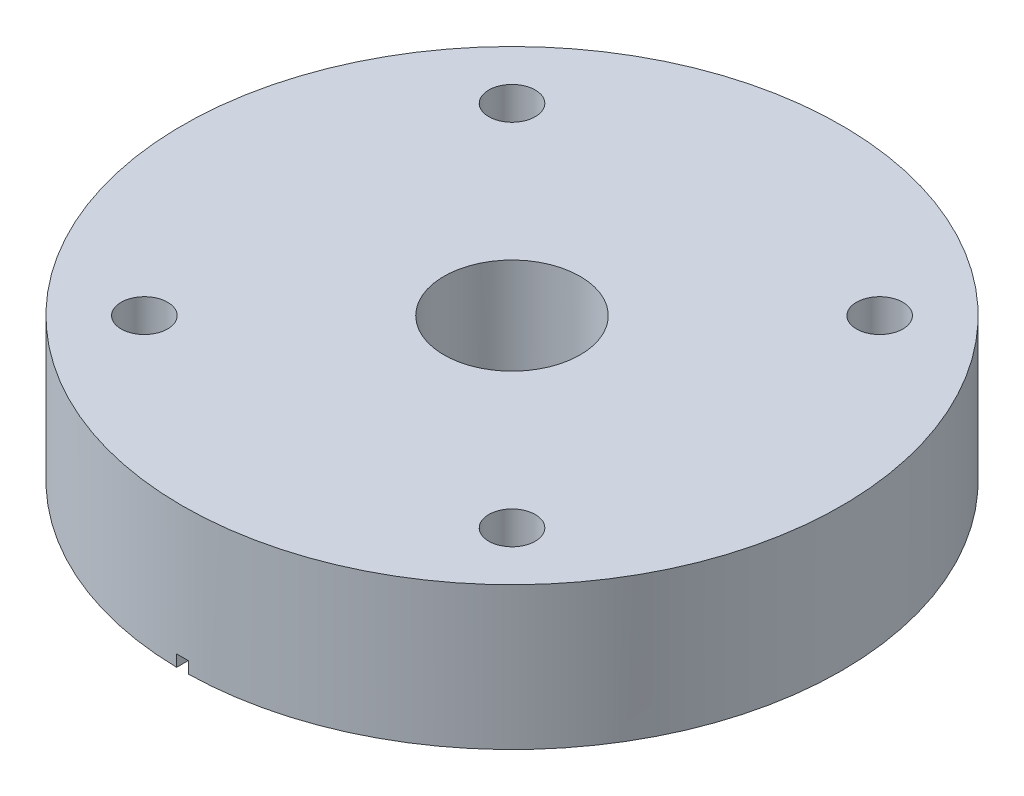
SolidWorks part; units mm, degrees
material "1060 Alloy"
ref_plane "Front" through (0, 0, 0) normal (0, 0, 1) x (1, 0, 0)
ref_plane "Top" through (0, 0, 0) normal (0, 1, 0) x (1, 0, 0)
ref_plane "Right" through (0, 0, 0) normal (1, 0, 0) x (0, 0, -1)
sketch "Sketch1" plane through (0, 0, 0) normal (0, 1, 0) x (1, 0, 0)
  line L0 (0, 0) -> (0, 44.45) construction
  circle A0 centre (-31.4309, 31.4309) radius 3.9688
  circle A1 centre (31.4309, 31.4309) radius 3.9687
  circle A2 centre (31.4309, -31.4309) radius 3.9687
  circle A3 centre (-31.4309, -31.4309) radius 3.9688
  circle A4 centre (0, 0) radius 10.1459
  arc A5 (-24.1039, 40.8157) -> (-40.8157, 24.1039) centre (-31.4309, 31.4309) ccw construction
  arc A6 (40.8157, 24.1039) -> (24.1039, 40.8157) centre (31.4309, 31.4309) ccw construction
  arc A7 (24.1039, -40.8157) -> (40.8157, -24.1039) centre (31.4309, -31.4309) ccw construction
  arc A8 (-40.8157, -24.1039) -> (-24.1039, -40.8157) centre (-31.4309, -31.4309) ccw construction
  arc A9 (-40.2313, 18.9009) -> (-40.2313, -18.9009) centre (0, 0) ccw construction
  arc A10 (-18.9009, -40.2313) -> (18.9009, -40.2313) centre (0, 0) ccw construction
  arc A11 (40.2313, -18.9009) -> (40.2313, 18.9009) centre (0, 0) ccw construction
  arc A12 (-18.9009, 40.2313) -> (-24.1039, 40.8157) centre (-21.027, 44.7568) cw construction
  arc A13 (18.9009, 40.2313) -> (-18.9009, 40.2313) centre (0, 0) ccw construction
  arc A14 (24.1039, 40.8157) -> (18.9009, 40.2313) centre (21.027, 44.7568) cw construction
  arc A15 (40.8157, 24.1039) -> (40.2313, 18.9009) centre (44.7568, 21.027) ccw construction
  arc A16 (40.2313, -18.9009) -> (40.8157, -24.1039) centre (44.7568, -21.027) ccw construction
  arc A17 (24.1039, -40.8157) -> (18.9009, -40.2313) centre (21.027, -44.7568) ccw construction
  arc A18 (-18.9009, -40.2313) -> (-24.1039, -40.8157) centre (-21.027, -44.7568) ccw construction
  arc A19 (-40.2313, -18.9009) -> (-40.8157, -24.1039) centre (-44.7568, -21.027) cw construction
  arc A20 (-40.2313, 18.9009) -> (-40.8157, 24.1039) centre (-44.7568, 21.027) ccw construction
  circle A21 centre (0, 0) radius 56.3562
  point P0 (0, 0)
  point P17 (0, 0)
  point P27 (0, 0)
  dimension "D5" = 7.9375
  dimension "D6" = 20.2918
  dimension "D1" = 5
  dimension "D2" = 11.9062
  dimension "D3" = 44.45
  dimension "D4" = 4
  dimension "D8" = 4
extrude "body and main holes" add sketch "Sketch1" along normal blind 24.4122
sketch "Sketch3" plane through (0, 24.4122, 0) normal (0, -1, 0) x (1, 0, 0)
  circle A0 centre (0, 0) radius 11.6459
  dimension "D1" = 23.2918
extrude "seal bore" cut sketch "Sketch3" along normal blind 22.4122
sketch "Sketch4" plane through (0, 0, 0) normal (0, -1, 0) x (1, 0, 0)
  line L0 (0, 0) -> (0, 44.45) construction
  line L2 (-1, 56.3563) -> (1, 56.3563)
  line L3 (-1, 56.3563) -> (-1, -56.3562)
  line L4 (-1, -56.3562) -> (1, -56.3562)
  line L5 (1, 56.3563) -> (1, -56.3562)
  line L6 (-1, 56.3563) -> (1, -56.3562) construction
  line L7 (-1, -56.3562) -> (1, 56.3563) construction
  circle A2 centre (0, 0) radius 56.3562 construction
  point P6 (0, 0)
  dimension "D1" = 2
extrude "vent slot" cut sketch "Sketch4" against normal blind 2
equation "\"D3@Sketch1\"=\"square plate bolt pattern diameter\"/2"
equation "\"D1@body and main holes\" = \"lower seal plate thickness\""
equation "\"D1@Sketch3\" = \"lower seal OD\""
equation "\"D1@seal bore\" = \"lower seal bore\""
equation "\"D5@Sketch1\"=\"m8 clearance\""
equation "\"D6@Sketch1\" = \"lower seal plate lip ID\""
equation "\"square plate bolt pattern diameter\"= 3.5in"
equation "\"square plate bolt bore\"= \"m8 clearance\""
equation "\"square plate bolt head diameter\"= 13.5mm"
equation "\"motor OD\"= 64mm"
equation "\"m6 clearance\"= 0.234375in\t'this is 15/64 bit = 5.95mm, could use 6mm bit, B bit for 6.04mm or 1/4 bit for 6.35mm"
equation "\"m6 tap\"= 5mm\t\t\t'5mm is appropriate, could use 13/64 or #5,6,7"
equation "\"m6 head bore diameter\"= 11mm\t\t"
equation "\"m6 head bore depth\"= 7mm\t'actual is 6mm"
equation "\"m8 clearance\"= 0.3125in\t'this is 5/16in for 7.93mm, could use 8mm, O,P, or 21/64"
equation "\"m8 tap\"= 0.265625in\t\t'this is 17/64 for 6.746875mm"
equation "\"m8 head bore diameter\"= 14mm"
equation "\"m8 head bore depth\"= 9mm\t'actual is 8mm"
equation "\"lower seal OD\"= .917in\t\t'this is https://www.mcmaster.com/#9281k121/=174001b"
equation "\"lower seal ID\"= .375in"
equation "\"lower seal depth\"= .625in + .218in"
equation "\"lower seal bore\"= \"lower seal depth\" + 1mm"
equation "\"impeller upper clearance\"= .5mm"
equation "\"impeller bottom clearance\"= .5mm"
equation "\"impeller dowel diameter\"= 2mm"
equation "\"impeller shaft bore depth\"= 12mm"
equation "\"impeller shaft bore\"= 8mm"
equation "\"impeller dowel length\"= 2mm*2 + \"impeller shaft bore\""
equation "\"square plate bolt head depth\"= 8mm"
equation "\"lower seal plate lip depth\"= 2mm"
equation "\"lower seal plate lip ID\"= \"lower seal OD\" - 3mm"
equation "\"lower seal plate thickness\"= \"lower seal plate lip depth\" + \"lower seal bore\""
equation "\"shaft coupler section diameter\"= 8mm"
equation "\"shaft bearing stop length\"= 3mm"
equation "\"shaft lower seal section diameter\"= \"lower seal ID\""
equation "\"shaft lower seal section length\"= \"lower seal plate thickness\" + 1mm"
equation "\"shaft impeller section diameter\"= \"impeller shaft bore\""
equation "\"upper seal plate pressure tap diameter\"= .328125in \t'this is 21/64 drill for a 1/8 ANPT tap"
equation "\"motor mount post radius\"= ( 3 * \"square plate bolt bore\" ) / 2"
